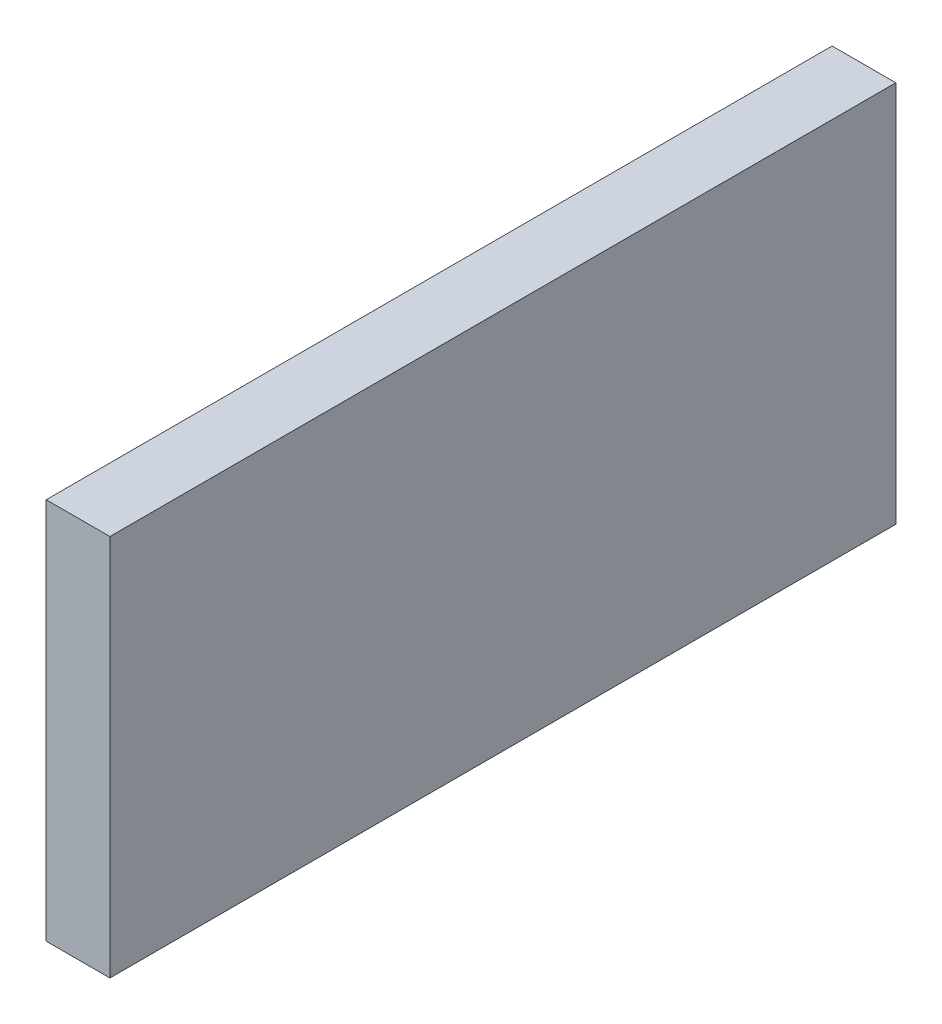
SolidWorks part; units mm, degrees
ref_plane "Front Plane" through (0, 0, 0) normal (0, 0, 1) x (1, 0, 0)
ref_plane "Top Plane" through (0, 0, 0) normal (0, 1, 0) x (1, 0, 0)
ref_plane "Right Plane" through (0, 0, 0) normal (1, 0, 0) x (0, 0, -1)
sketch "Sketch1" plane through (0, 0, 0) normal (0, 1, 0) x (1, 0, 0)
  line L1 (0, 0) -> (3, 0)
  line L6 (0, 0) -> (0, 37)
  line L7 (0, 37) -> (3, 37)
  line L8 (3, 0) -> (3, 37)
  dimension "D1" = 37
  dimension "D2" = 3
extrude "Boss-Extrude1" add sketch "Sketch1" along normal blind 18
